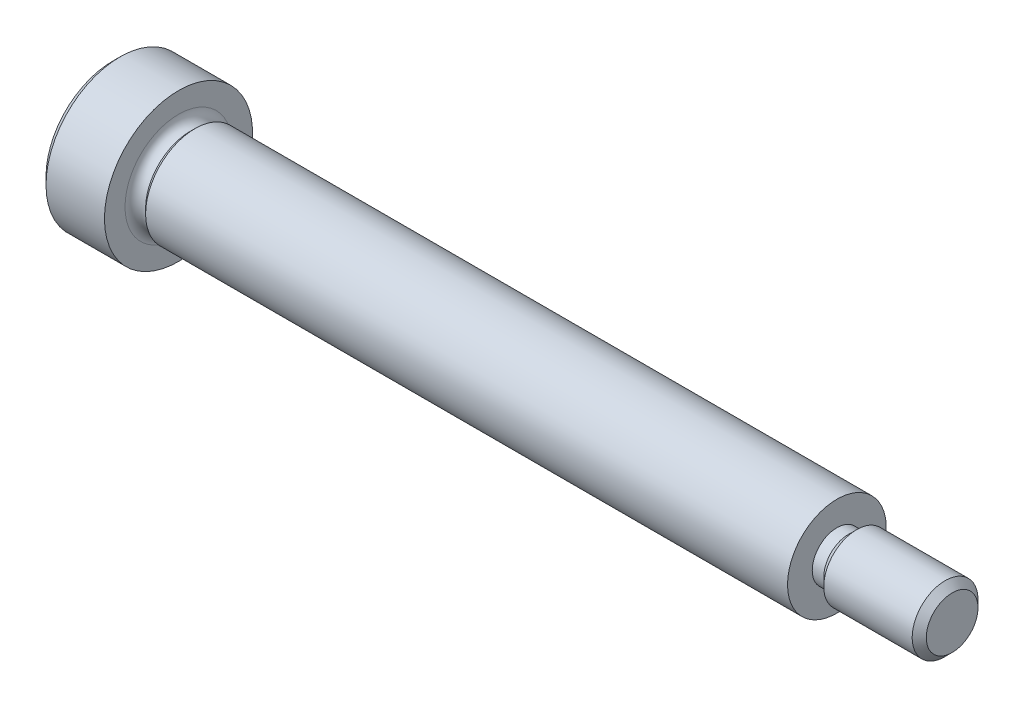
SolidWorks part; units mm, degrees
ref_plane "Plan de face" through (0, 0, 0) normal (0, 0, 1) x (1, 0, 0)
ref_plane "Plan de dessus" through (0, 0, 0) normal (0, 1, 0) x (1, 0, 0)
ref_plane "Plan de droite" through (0, 0, 0) normal (1, 0, 0) x (0, 0, -1)
ref_plane "Plan1" through (0, 0, 0) normal (0, 0, 1) x (1, 0, 0)
sketch "Esquisse1" plane through (0, 0, 0) normal (0, 0, 1) x (1, 0, 0)
  line L0 (-1.134, 0) -> (-2, 1.5)
  line L1 (-2, 1.5) -> (-4, 1.5)
  line L2 (-4, 1.5) -> (-4, 4.05)
  line L3 (-4, 4.05) -> (-3.55, 4.5)
  line L4 (-3.55, 4.5) -> (0, 4.5)
  line L5 (0, 4.5) -> (0, 3.25)
  line L6 (0.7, 2.7) -> (1, 3)
  line L7 (1, 3) -> (40, 3)
  line L8 (40, 3) -> (40, 1.5)
  line L9 (40, 1.5) -> (40.7, 1.5)
  line L10 (40.7, 1.5) -> (41.2, 2)
  line L11 (41.2, 2) -> (46.5705, 2)
  line L12 (46.5705, 2) -> (47, 1.5705)
  line L13 (47, 1.5705) -> (47, 0)
  line L14 (47, 0) -> (-1.134, 0)
  line L15 (47, 0) -> (-1.134, 0) construction
  arc A0 (0, 3.25) -> (0.7, 2.7) centre (0.5749, 3.2612) ccw
revolve "Révolution1" add sketch "Esquisse1" angle 360 about L15
cosmetic thread "Représentation de filetage1" parameters "D1"=5.8, "D2"=3.141
ref_plane "Plan2" through (-4, 0, 0) normal (1, 0, 0) x (0, 0, -1)
sketch "Esquisse2" plane through (-4, 0, 0) normal (1, 0, 0) x (0, 0, -1)
  line L0 (-1.5, 0.866) -> (-1.5, -0.866)
  line L1 (-1.5, -0.866) -> (0, -1.7321)
  line L2 (0, -1.7321) -> (1.5, -0.866)
  line L3 (1.5, -0.866) -> (1.5, 0.866)
  line L4 (1.5, 0.866) -> (0, 1.7321)
  line L5 (0, 1.7321) -> (-1.5, 0.866)
extrude "Enlèv. mat.-Extru.1" cut sketch "Esquisse2" along normal blind 2
